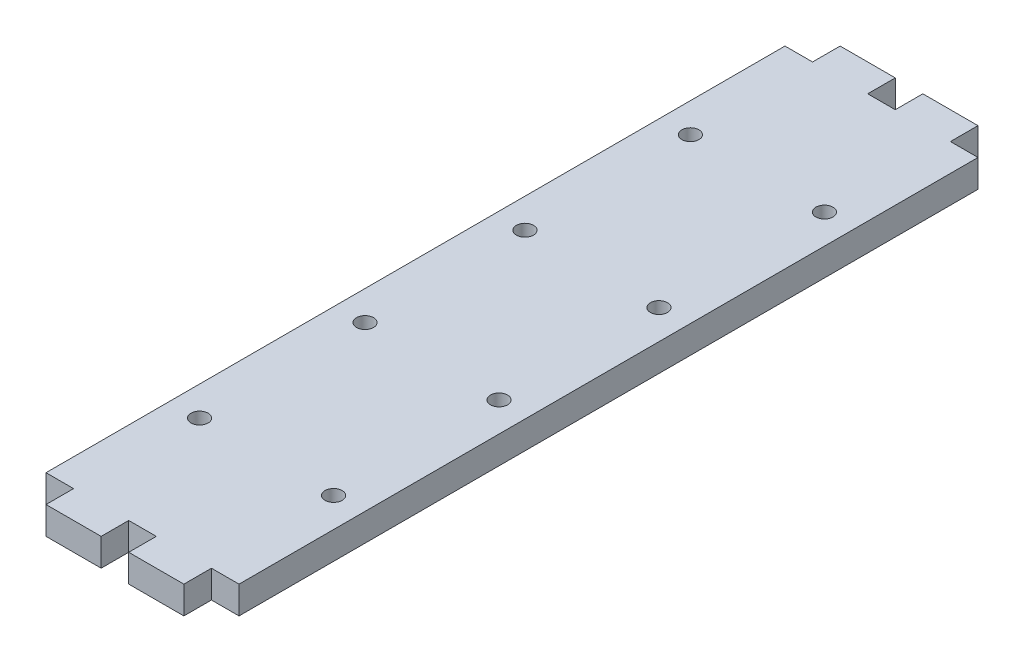
SolidWorks part; units mm, degrees
ref_plane "Front Plane" through (0, 0, 0) normal (0, 0, 1) x (1, 0, 0)
ref_plane "Top Plane" through (0, 0, 0) normal (0, 1, 0) x (1, 0, 0)
ref_plane "Right Plane" through (0, 0, 0) normal (1, 0, 0) x (0, 0, -1)
sketch "Sketch1" plane through (0, 0, 0) normal (0, 1, 0) x (1, 0, 0)
  line L1 (-10, -78.7886) -> (0, -78.7886)
  line L2 (0, -78.7886) -> (0, -73.7886)
  line L3 (0, -73.7886) -> (5, -73.7886)
  line L4 (5, -73.7886) -> (5, -78.7886)
  line L5 (5, -78.7886) -> (15, -78.7886)
  line L7 (15, 65.2114) -> (5, 65.2114)
  line L8 (5, 65.2114) -> (5, 60.2114)
  line L9 (5, 60.2114) -> (0, 60.2114)
  line L10 (0, 60.2114) -> (0, 65.2114)
  line L11 (0, 65.2114) -> (-10, 65.2114)
  line L14 (20, 60.2114) -> (20, -73.7886)
  line L16 (-15, 60.2114) -> (-15, -73.7886)
  line L18 (15, -78.7886) -> (15, -73.7886)
  line L19 (15, -73.7886) -> (20, -73.7886)
  line L20 (-10, -78.7886) -> (-10, -73.7886)
  line L21 (-10, -73.7886) -> (-15, -73.7886)
  line L22 (15, 65.2114) -> (15, 60.2114)
  line L23 (15, 60.2114) -> (20, 60.2114)
  line L24 (-10, 65.2114) -> (-10, 60.2114)
  line L25 (-10, 60.2114) -> (-15, 60.2114)
  line L26 (20, -6.7886) -> (-10, -6.7886) construction
  circle A0 centre (14.65, 37.7114) radius 1.55
  circle A1 centre (14.65, 7.7114) radius 1.55
  circle A2 centre (-9.65, 37.7114) radius 1.55
  circle A3 centre (-9.65, 7.7114) radius 1.55
  circle A4 centre (-9.65, -21.2886) radius 1.55
  circle A5 centre (-9.65, -51.2886) radius 1.55
  circle A6 centre (14.65, -21.2886) radius 1.55
  circle A7 centre (14.65, -51.2886) radius 1.55
  point P17 (2.5, 22.7114)
  dimension "D1" = 144
  dimension "D2" = 10
  dimension "D3" = 5
  dimension "D4" = 10
  dimension "D5" = 10
  dimension "D6" = 10
  dimension "D7" = 5
  dimension "D8" = 5
  dimension "D9" = 144
  dimension "D10" = 5
  dimension "D11" = 5
  dimension "D12" = 30
  dimension "D13" = 24.3
  dimension "D14" = 5
  dimension "D15" = 42.5
  dimension "D16" = 35
  dimension "D17" = 5
  dimension "D18" = 5
  dimension "D19" = 17.5
extrude "Boss-Extrude1" add sketch "Sketch1" along normal blind 5
